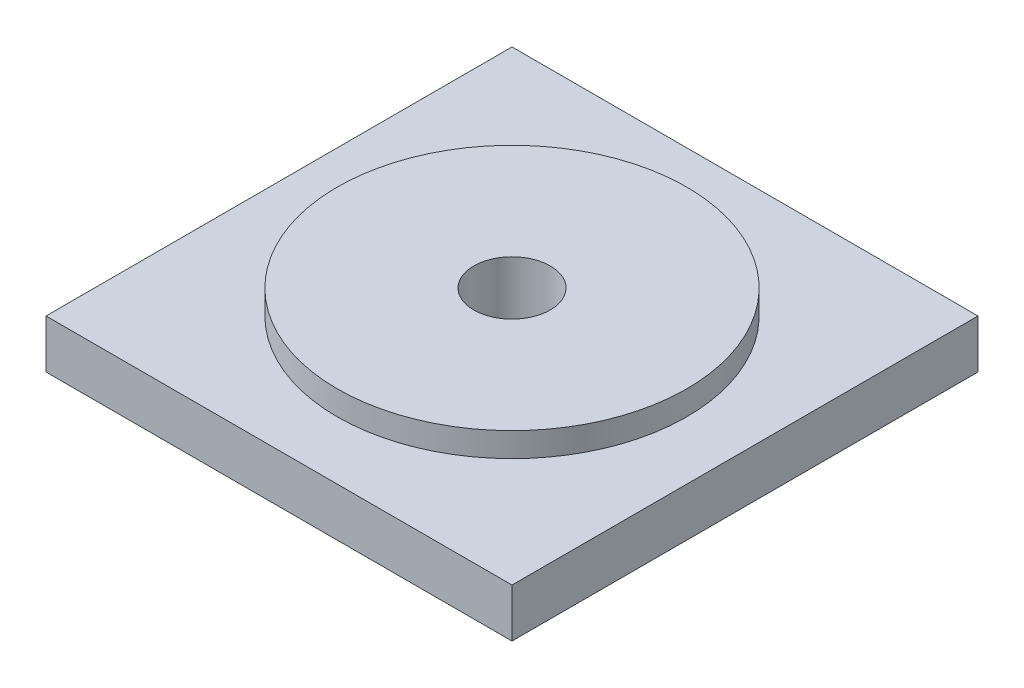
SolidWorks part; units mm, degrees
ref_plane "Front Plane" through (0, 0, 0) normal (0, 0, 1) x (1, 0, 0)
ref_plane "Top Plane" through (0, 0, 0) normal (0, 1, 0) x (1, 0, 0)
ref_plane "Right Plane" through (0, 0, 0) normal (1, 0, 0) x (0, 0, -1)
sketch "Sketch1" plane through (0, 0, 0) normal (0, 1, 0) x (1, 0, 0)
  line L1 (0, 0) -> (24.384, 0)
  line L2 (0, 0) -> (0, -24.384)
  line L3 (0, -24.384) -> (24.384, -24.384)
  line L4 (24.384, 0) -> (24.384, -24.384)
  dimension "D1" = 24.384
  dimension "D2" = 24.384
extrude "Boss-Extrude1" add sketch "Sketch1" along normal blind 2.54
sketch "Sketch2" plane through (0, 2.54, 0) normal (0, 1, 0) x (1, 0, 0)
  line L1 (0, 0) -> (0, -24.384) construction
  line L2 (24.384, 0) -> (0, 0) construction
  circle A0 centre (12.192, -12.192) radius 9.144
  dimension "D1" = 18.288
  dimension "D2" = 12.192
  dimension "D3" = 12.192
extrude "Boss-Extrude2" add sketch "Sketch2" along normal blind 1.27
sketch "Sketch3" plane through (0, 3.81, 0) normal (0, 1, 0) x (1, 0, 0)
  circle A0 centre (12.192, -12.192) radius 2
  dimension "D1" = 4
extrude "Cut-Extrude1" cut sketch "Sketch3" against normal through all
